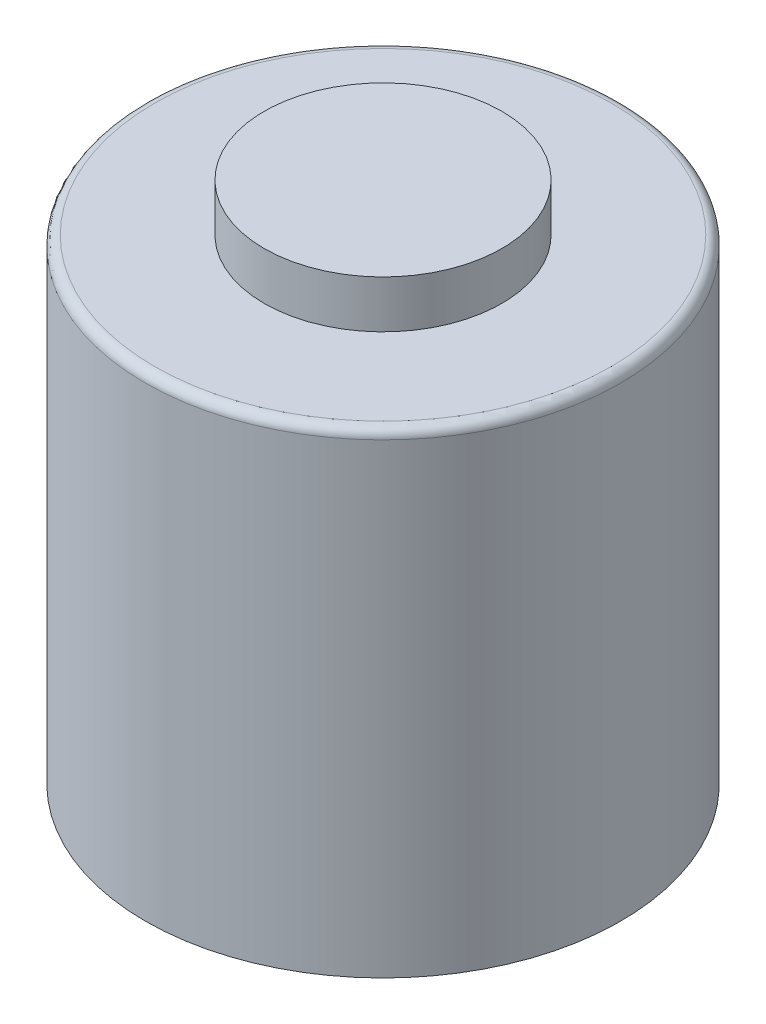
SolidWorks part; units mm, degrees
ref_plane "Front Plane" through (0, 0, 0) normal (0, 0, 1) x (1, 0, 0)
ref_plane "Top Plane" through (0, 0, 0) normal (0, 1, 0) x (1, 0, 0)
ref_plane "Right Plane" through (0, 0, 0) normal (1, 0, 0) x (0, 0, -1)
sketch "Sketch1" plane through (0, 0, 0) normal (0, 1, 0) x (1, 0, 0)
  circle A0 centre (0, 0) radius 250
  dimension "D1" = 500
extrude "Boss-Extrude1" add sketch "Sketch1" along normal blind 500
sketch "Sketch2" plane through (0, 500, 0) normal (0, 1, 0) x (1, 0, 0)
  circle A0 centre (0, 0) radius 125
  dimension "D1" = 250
extrude "Boss-Extrude2" add sketch "Sketch2" along normal blind 50
fillet "Fillet1" radius 10 1 edges at (0, 500, 250)
